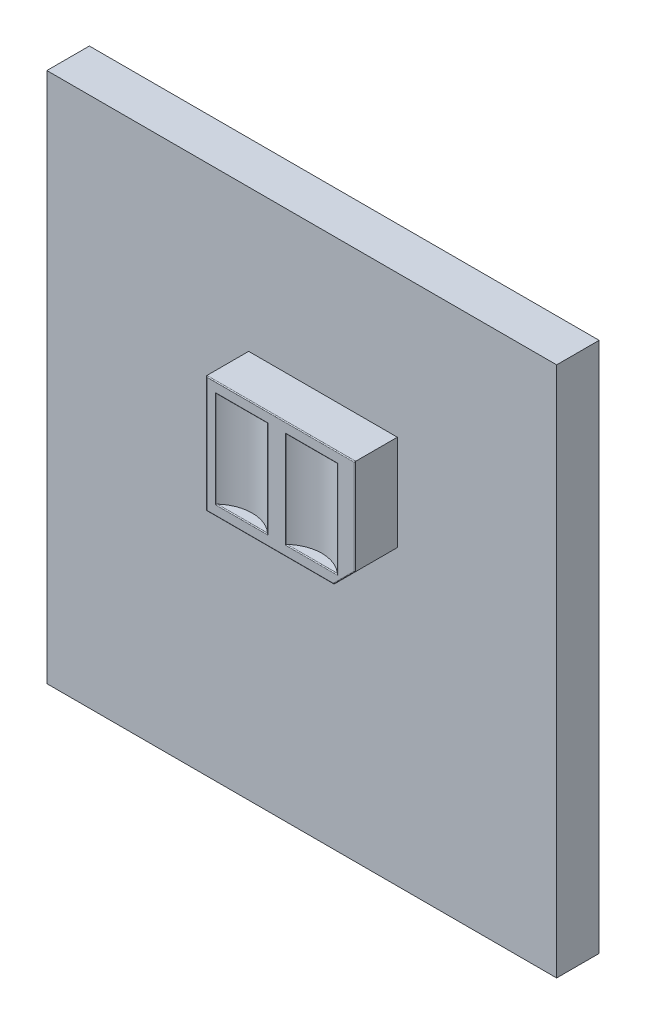
SolidWorks part; units mm, degrees
ref_plane "Face" through (0, 0, 0) normal (0, 0, 1) x (1, 0, 0)
ref_plane "Dessus" through (0, 0, 0) normal (0, 1, 0) x (1, 0, 0)
ref_plane "Droite" through (0, 0, 0) normal (1, 0, 0) x (0, 0, -1)
sketch "Esquisse1" plane through (0, 0, 0) normal (0, 0, 1) x (1, 0, 0)
  line L1 (-6, 6.25) -> (6, 6.25)
  line L2 (-6, 6.25) -> (-6, -6.25)
  line L3 (-6, -6.25) -> (6, -6.25)
  line L4 (6, 6.25) -> (6, -6.25)
  dimension "D1" = 6.25
  dimension "D2" = 12.5
  dimension "D3" = 6
  dimension "D4" = 12
extrude "Extrusion1" add sketch "Esquisse1" along normal blind 1
sketch "Esquisse5"
sketch "Esquisse3" plane through (0, 0, 0) normal (0, 0, 1) x (1, 0, 0)
  line L0 (-1.25, 2.9) -> (2.25, 2.9)
  line L1 (2.25, 2.9) -> (2.25, 0.65)
  line L2 (2.25, 0.65) -> (1.75, 0.15)
  line L3 (1.75, 0.15) -> (-1.25, 0.15)
  line L4 (-1.25, 0.15) -> (-1.25, 2.9)
  line L5 (-6, -6.25) -> (6, -6.25) construction
  line L6 (6, -6.25) -> (6, 6.25) construction
  point P9 (2.25, 0.15)
  dimension "D1" = 6.4
  dimension "D2" = 2.75
  dimension "D3" = 3.5
  dimension "D4" = 3.75
extrude "Extrusion2" add sketch "Esquisse3" along normal blind 2
ref_plane "Plan1" through (0, 0.4, 0) normal (0, -1, 0) x (1, 0, 0)
sketch "Esquisse4" plane through (0, 0.4, 0) normal (0, -1, 0) x (1, 0, 0)
  line L0 (0.4084, 2.8941) -> (0.4084, -0.6438) construction
  line L1 (0.6194, 2) -> (1.8396, 2)
  line L2 (-1.25, 2) -> (1.75, 2) construction
  line L3 (0.1974, 2) -> (-1.0228, 2)
  line L4 (1.75, 2) -> (2.25, 2) construction
  arc A0 (0.6194, 2) -> (1.8396, 2) centre (1.2295, 2.6375) ccw
  arc A1 (0.1974, 2) -> (-1.0228, 2) centre (-0.4127, 2.6375) cw
extrude "Enlèv. mat.-Extru.1" cut sketch "Esquisse4" against normal blind 2.25
fillet "Congé1" radius 0.02
